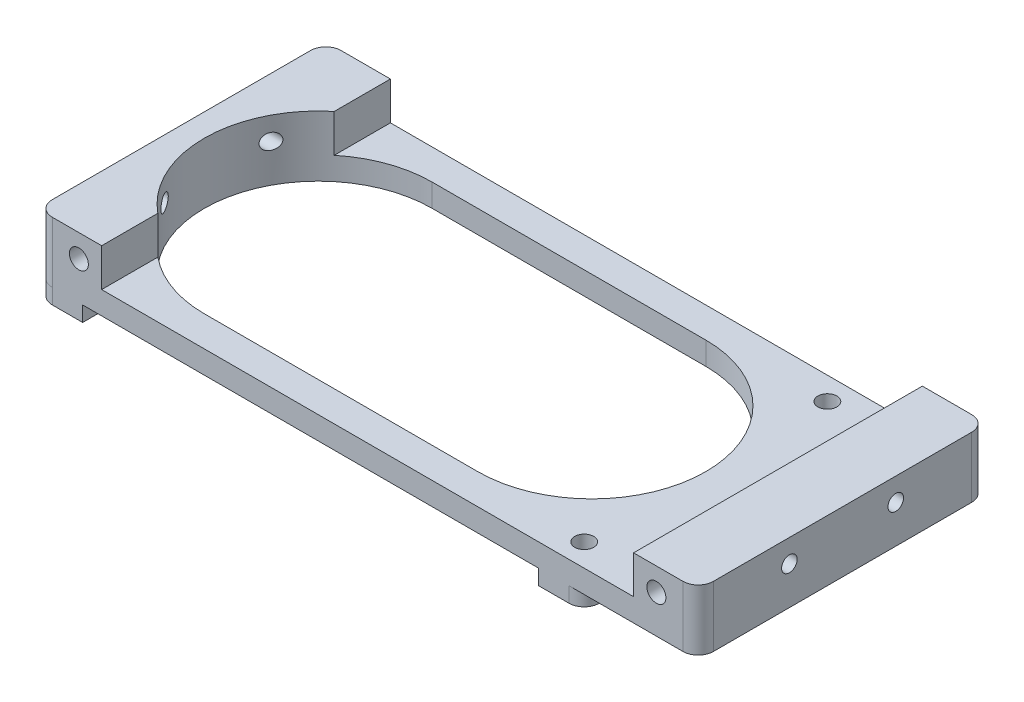
SolidWorks part; units mm, degrees
ref_plane "Front Plane" through (0, 0, 0) normal (0, 0, 1) x (1, 0, 0)
ref_plane "Top Plane" through (0, 0, 0) normal (0, 1, 0) x (1, 0, 0)
ref_plane "Right Plane" through (0, 0, 0) normal (1, 0, 0) x (0, 0, -1)
sketch "Sketch2" plane through (0, 0, 11.2) normal (0, 0, 1) x (1, 0, 0)
  line L1 (-84.0653, 85.9519) -> (-75.5653, 85.9519)
  line L2 (-84.0653, 85.9519) -> (-84.0653, 77.9519)
  line L3 (-84.0653, 77.9519) -> (2.9347, 77.9519)
  line L4 (2.9347, 85.9519) -> (2.9347, 77.9519)
  line L5 (-71.5653, 86.4519) -> (-82.0653, 86.4519) construction
  line L14 (-5.5653, 85.9519) -> (2.9347, 85.9519)
  line L16 (-75.5653, 85.9519) -> (-75.5653, 80.9519)
  line L17 (-75.5653, 80.9519) -> (-5.5653, 80.9519)
  line L18 (-5.5653, 85.9519) -> (-5.5653, 80.9519)
  dimension "D1" = 0.5
  dimension "D2" = 5.5
  dimension "D3" = 5.5
  dimension "D4" = 8
  dimension "D5" = 5
  dimension "D6" = 8.5
  dimension "D7" = 8.5
extrude "Boss-Extrude1" add sketch "Sketch2" along normal blind 38
fillet "Fillet3" radius 2 4 edges at (-84.0653, 81.9519, 49.2) (-84.0653, 81.9519, 11.2) (2.9347, 81.9519, 11.2) (2.9347, 81.9519, 49.2)
sketch "Sketch3" plane through (0, 80.9519, 0) normal (0, 1, 0) x (1, 0, 0)
  line L0 (-84.0653, -47.2) -> (-84.0653, -13.2) construction
  line L1 (-5.5653, -11.2) -> (-75.5653, -11.2) construction
  line L2 (-66.0653, -15.2) -> (-30.0653, -15.2)
  line L4 (-66.0653, -45.2) -> (-30.0653, -45.2)
  arc A0 (-30.0653, -45.2) -> (-30.0653, -15.2) centre (-30.0653, -30.2) ccw
  arc A1 (-66.0653, -15.2) -> (-66.0653, -45.2) centre (-66.0653, -30.2) ccw
  dimension "D1" = 30
  dimension "D2" = 18
  dimension "D3" = 36
  dimension "D4" = 19
extrude "Cut-Extrude1" cut sketch "Sketch3" against normal through all and the other way through all
hole_wizard "M3x0.5 Tapped Hole2" positions "Sketch6" profile "Sketch5" tap size "M3x0.5" standard "Ansi Metric"
sketch "Sketch6" plane through (0, 0, 11.2) normal (0, 0, -1) x (-1, 0, 0)
  line L1 (75.5653, 80.9519) -> (75.5653, 85.9519) construction
  line L2 (5.5653, 85.9519) -> (5.5653, 80.9519) construction
  line L3 (75.5653, 85.9519) -> (82.0653, 85.9519) construction
  line L4 (-0.9347, 85.9519) -> (5.5653, 85.9519) construction
  point P0 (78.5653, 82.9519)
  point P5 (2.5653, 82.9519)
  dimension "D1" = 3
  dimension "D2" = 3
  dimension "D3" = 3
  dimension "D4" = 3
sketch "Sketch5" plane through (-78.5653, 82.9519, 11.2) normal (1, 0, 0) x (0, 1, 0)
  line L0 (0, 0) -> (0, 8.2511)
  line L1 (0, 8.2511) -> (1.25, 7.5)
  line L2 (1.25, 7.5) -> (1.25, 0)
  line L5 (1.25, 0) -> (0, 0)
  line L10 (0, 8.2511) -> (-1.25, 7.5) construction
  line L11 (0, -6.35) -> (0, 107.95) construction
  dimension "Tap Drill Dia." = 2.5
  dimension "Tap Drill Depth" = 7.5
  dimension "Drill Angle" = 118
cosmetic thread "Hole Thread3" parameters "D1"=6, "D2"=3
cosmetic thread "Hole Thread4" parameters "D1"=6, "D2"=3
hole_wizard "M3x0.5 Tapped Hole3" positions "Sketch8" profile "Sketch7" tap size "M3x0.5" standard "Ansi Metric"
sketch "Sketch8" plane through (0, 0, 49.2) normal (0, 0, 1) x (1, 0, 0)
  line L0 (-5.5653, 85.9519) -> (-5.5653, 80.9519) construction
  line L2 (-75.5653, 85.9519) -> (-82.0653, 85.9519) construction
  line L3 (-75.5653, 80.9519) -> (-75.5653, 85.9519) construction
  line L4 (0.9347, 85.9519) -> (-5.5653, 85.9519) construction
  point P0 (-2.5653, 82.9519)
  point P1 (-78.5653, 82.9519)
  dimension "D1" = 3
  dimension "D2" = 3
  dimension "D3" = 3
  dimension "D4" = 3
sketch "Sketch7" plane through (-2.5653, 82.9519, 49.2) normal (1, 0, 0) x (0, -1, 0)
  line L0 (0, 0) -> (0, 8.2511)
  line L1 (0, 8.2511) -> (1.25, 7.5)
  line L2 (1.25, 7.5) -> (1.25, 0)
  line L5 (1.25, 0) -> (0, 0)
  line L10 (0, 8.2511) -> (-1.25, 7.5) construction
  line L11 (0, -6.35) -> (0, 107.95) construction
  dimension "Tap Drill Dia." = 2.5
  dimension "Tap Drill Depth" = 7.5
  dimension "Drill Angle" = 118
cosmetic thread "Hole Thread5" parameters "D1"=6, "D2"=3
cosmetic thread "Hole Thread6" parameters "D1"=6, "D2"=3
hole_wizard "M2.5x0.45 Tapped Hole1" positions "Sketch10" profile "Sketch9" tap size "M2.5x0.45" standard "Ansi Metric"
sketch "Sketch10" plane through (-84.0653, 0, 0) normal (-1, 0, 0) x (0, 0, 1)
  line L0 (30.2, 85.6523) -> (30.2, 71.6474) construction
  line L3 (47.2, 85.9519) -> (13.2, 85.9519) construction
  line L4 (49.2, 85.9519) -> (49.2, 77.9519) construction
  line L5 (11.2, 77.9519) -> (11.2, 85.9519) construction
  point P0 (37.2, 82.9519)
  point P1 (23.2, 82.9519)
  dimension "D1" = 12
  dimension "D2" = 3
  dimension "D3" = 3
  dimension "D4" = 12
sketch "Sketch9" plane through (-84.0653, 82.9519, 37.2) normal (0, 1, 0) x (0, 0, 1)
  line L0 (0, 0) -> (0, 6.9659)
  line L1 (0, 6.9659) -> (1.025, 6.35)
  line L2 (1.025, 6.35) -> (1.025, 0)
  line L5 (1.025, 0) -> (0, 0)
  line L10 (0, 6.9659) -> (-1.025, 6.35) construction
  line L11 (0, -6.35) -> (0, 107.95) construction
  dimension "Tap Drill Dia." = 2.05
  dimension "Tap Drill Depth" = 6.35
  dimension "Drill Angle" = 118
cosmetic thread "Hole Thread7" parameters "D1"=5, "D2"=2.5
cosmetic thread "Hole Thread8" parameters "D1"=5, "D2"=2.5
hole_wizard "M2.5x0.45 Tapped Hole2" positions "Sketch12" profile "Sketch11" tap size "M2.5x0.45" standard "Ansi Metric"
sketch "Sketch12" plane through (2.9347, 0, 0) normal (1, 0, 0) x (0, 0, -1)
  line L0 (-11.2, 85.9519) -> (-11.2, 77.9519) construction
  line L1 (-47.2, 85.9519) -> (-13.2, 85.9519) construction
  point P0 (-23.2, 82.9519)
  point P1 (-37.2, 82.9519)
  dimension "D1" = 12
  dimension "D2" = 3
  dimension "D3" = 3
  dimension "D4" = 14
sketch "Sketch11" plane through (2.9347, 82.9519, 23.2) normal (0, 1, 0) x (0, 0, -1)
  line L0 (0, 0) -> (0, 6.9659)
  line L1 (0, 6.9659) -> (1.025, 6.35)
  line L2 (1.025, 6.35) -> (1.025, 0)
  line L5 (1.025, 0) -> (0, 0)
  line L10 (0, 6.9659) -> (-1.025, 6.35) construction
  line L11 (0, -6.35) -> (0, 107.95) construction
  dimension "Tap Drill Dia." = 2.05
  dimension "Tap Drill Depth" = 6.35
  dimension "Drill Angle" = 118
cosmetic thread "Hole Thread9" parameters "D1"=5, "D2"=2.5
cosmetic thread "Hole Thread10" parameters "D1"=5, "D2"=2.5
sketch "Sketch13" plane through (0, 77.9519, 0) normal (0, -1, 0) x (1, 0, 0)
  line L1 (-84.0653, 11.2) -> (-78.0653, 11.2)
  line L2 (-84.0653, 11.2) -> (-84.0653, 17.2)
  line L3 (-84.0653, 17.2) -> (-78.0653, 17.2)
  line L4 (-78.0653, 11.2) -> (-78.0653, 17.2)
  line L5 (-84.0653, 47.2) -> (-84.0653, 13.2) construction
  line L6 (-84.0653, 49.2) -> (-78.0653, 49.2)
  line L7 (-84.0653, 49.2) -> (-84.0653, 43.2)
  line L8 (-84.0653, 43.2) -> (-78.0653, 43.2)
  line L10 (-78.0653, 49.2) -> (-78.0653, 43.2)
  line L11 (-82.0653, 49.2) -> (0.9347, 49.2) construction
  line L12 (-5.5653, 11.2) -> (-75.5653, 11.2) construction
  line L13 (-12.0653, 11.2) -> (-18.0653, 11.2)
  line L14 (-12.0653, 11.2) -> (-12.0653, 17.2)
  line L15 (-12.0653, 17.2) -> (-18.0653, 17.2)
  line L16 (-18.0653, 11.2) -> (-18.0653, 17.2)
  line L17 (-5.5653, 49.2) -> (-75.5653, 49.2) construction
  line L18 (-12.0653, 49.2) -> (-18.0653, 49.2)
  line L19 (-12.0653, 49.2) -> (-12.0653, 43.2)
  line L20 (-12.0653, 43.2) -> (-18.0653, 43.2)
  line L21 (-18.0653, 49.2) -> (-18.0653, 43.2)
  dimension "D1" = 6
  dimension "D2" = 6
  dimension "D3" = 6
  dimension "D4" = 6
  dimension "D5" = 6
  dimension "D6" = 6
  dimension "D7" = 60
  dimension "D8" = 60
  dimension "D9" = 6
  dimension "D10" = 6
extrude "Boss-Extrude3" add sketch "Sketch13" along normal blind 2
fillet "Fillet6" radius 2 8 edges at (-12.0653, 76.9519, 49.2) (-12.0653, 76.9519, 11.2) (-84.0653, 76.9519, 11.2) (-84.0653, 76.9519, 49.2) (-78.0653, 76.9519, 17.2) (-78.0653, 76.9519, 43.2) (-18.0653, 76.9519, 43.2) (-18.0653, 76.9519, 17.2)
hole_wizard "M3x0.5 Tapped Hole4" positions "Sketch15" profile "Sketch14" tap size "M3x0.5" standard "Ansi Metric"
sketch "Sketch15" plane through (0, 75.9519, 0) normal (0, -1, 0) x (1, 0, 0)
  line L0 (-12.0653, 17.2) -> (-16.0653, 17.2) construction
  line L1 (-18.0653, 15.2) -> (-18.0653, 11.2) construction
  line L2 (-18.0653, 49.2) -> (-18.0653, 45.2) construction
  line L4 (-16.0653, 43.2) -> (-12.0653, 43.2) construction
  line L5 (-84.0653, 43.2) -> (-80.0653, 43.2) construction
  line L7 (-78.0653, 45.2) -> (-78.0653, 49.2) construction
  line L8 (-80.0653, 17.2) -> (-84.0653, 17.2) construction
  line L9 (-84.0653, 17.2) -> (-84.0653, 13.2) construction
  point P0 (-15.0653, 46.2)
  point P1 (-15.0653, 14.2)
  point P3 (-81.0653, 14.2)
  point P5 (-81.0653, 46.2)
  dimension "D1" = 3
  dimension "D2" = 3
  dimension "D3" = 3
  dimension "D4" = 3
  dimension "D5" = 3
  dimension "D6" = 3
  dimension "D7" = 3
  dimension "D8" = 3
sketch "Sketch14" plane through (-15.0653, 75.9519, 46.2) normal (1, 0, 0) x (0, 0, -1)
  line L0 (0, 0) -> (0, 5.9511)
  line L1 (0, 5.9511) -> (1.25, 5.2)
  line L2 (1.25, 5.2) -> (1.25, 0)
  line L5 (1.25, 0) -> (0, 0)
  line L10 (0, 5.9511) -> (-1.25, 5.2) construction
  line L11 (0, -6.35) -> (0, 107.95) construction
  dimension "Tap Drill Dia." = 2.5
  dimension "Tap Drill Depth" = 5.2
  dimension "Drill Angle" = 118
cosmetic thread "Hole Thread11" parameters "D1"=5, "D2"=3
cosmetic thread "Hole Thread12" parameters "D1"=5, "D2"=3
cosmetic thread "Hole Thread13" parameters "D1"=5, "D2"=3
cosmetic thread "Hole Thread14" parameters "D1"=5, "D2"=3
